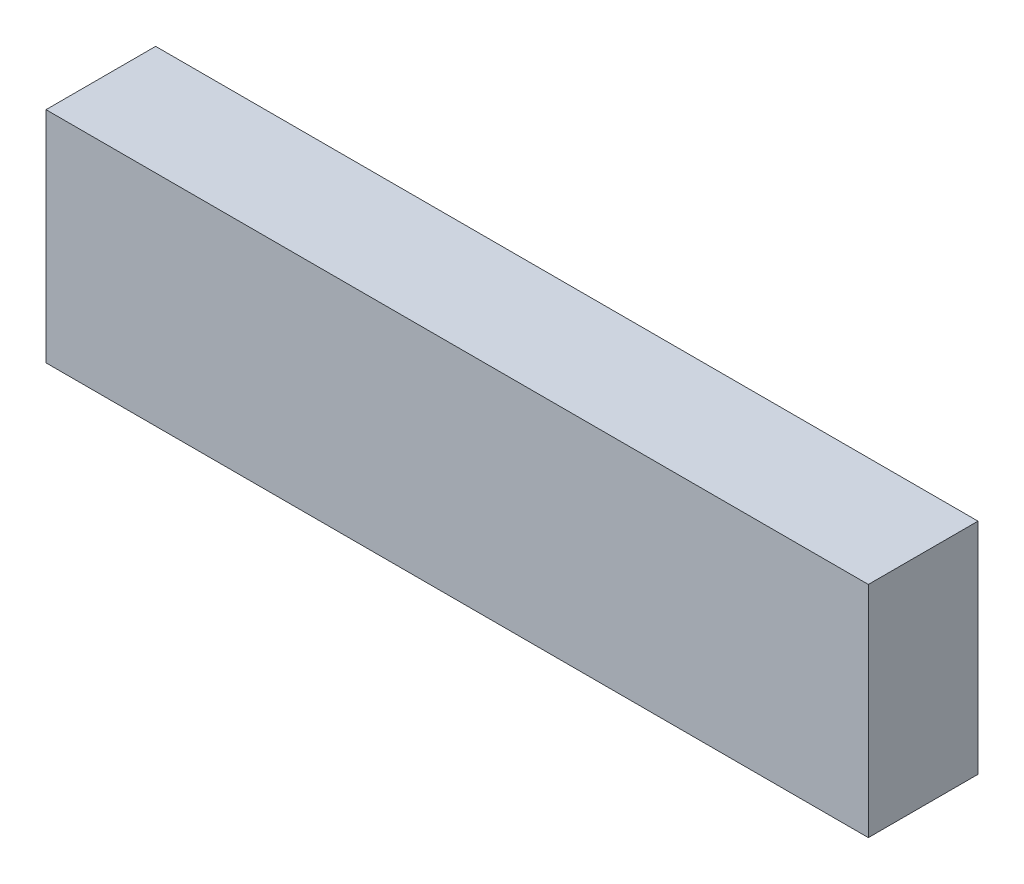
SolidWorks part; units mm, degrees
ref_plane "Front Plane" through (0, 0, 0) normal (0, 0, 1) x (1, 0, 0)
ref_plane "Top Plane" through (0, 0, 0) normal (0, 1, 0) x (1, 0, 0)
ref_plane "Right Plane" through (0, 0, 0) normal (1, 0, 0) x (0, 0, -1)
ref_plane "Plane1" through (0, 1, 0) normal (0, 1, 0) x (1, 0, 0)
sketch "Sketch1" plane through (0, 0, 0) normal (0, 1, 0) x (1, 0, 0)
  line L1 (25, -25) -> (-25, -25)
  line L2 (25, -25) -> (25, 25)
  line L3 (25, 25) -> (-25, 25)
  line L4 (-25, -25) -> (-25, 25)
  line L5 (25, -25) -> (-25, 25) construction
  line L6 (25, 25) -> (-25, -25) construction
  point P0 (0, 0)
  dimension "D1" = 50
  dimension "D2" = 50
sketch "Sketch5" plane through (0, 1, 0) normal (0, 1, 0) x (1, 0, 0)
  line L9 (-15, 2) -> (15, 2)
  line L10 (-15, 2) -> (-15, -2)
  line L11 (-15, -2) -> (15, -2)
  line L12 (15, 2) -> (15, -2)
  dimension "D1" = 4
  dimension "D2" = 30
  dimension "D3" = 2
  dimension "D4" = 15
extrude "Boss-Extrude4" add sketch "Sketch5" along normal blind 8
